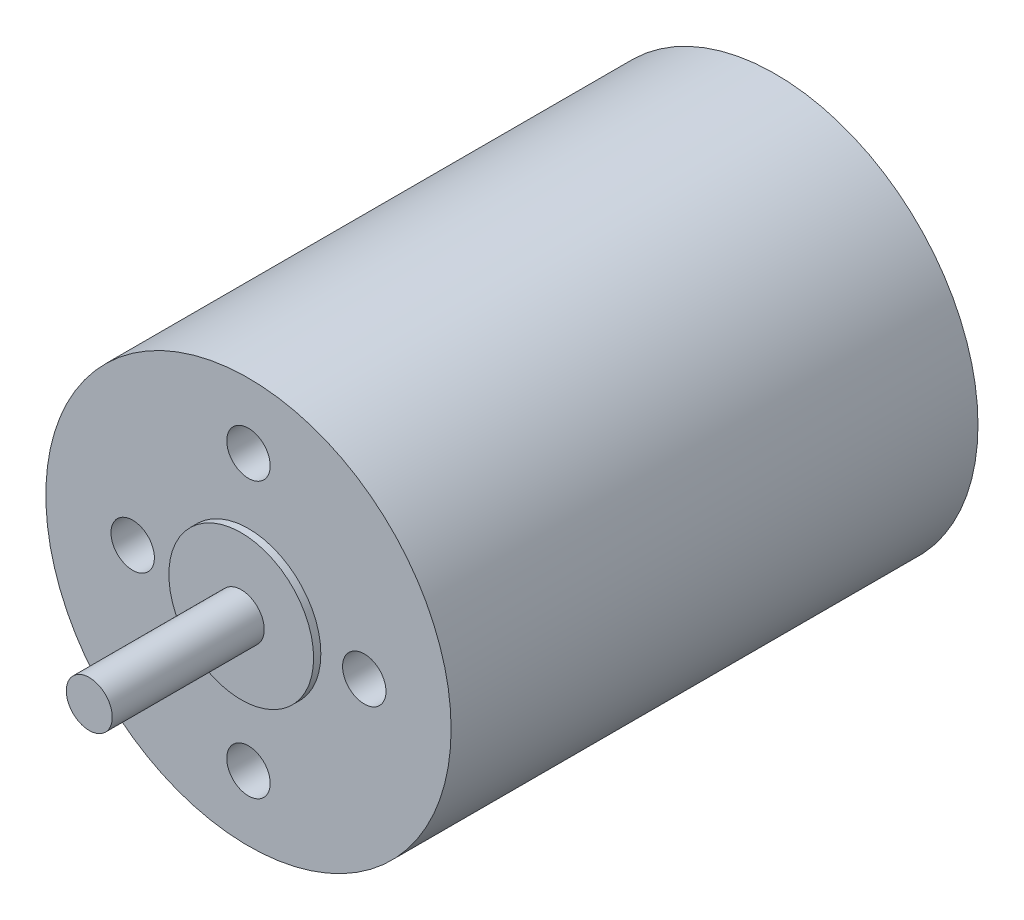
SolidWorks part; units mm, degrees
ref_plane "Front Plane" through (0, 0, 0) normal (0, 0, 1) x (1, 0, 0)
ref_plane "Top Plane" through (0, 0, 0) normal (0, 1, 0) x (1, 0, 0)
ref_plane "Right Plane" through (0, 0, 0) normal (1, 0, 0) x (0, 0, -1)
sketch "Sketch1" plane through (0, 0, 0) normal (0, 0, 1) x (1, 0, 0)
  circle A0 centre (0, 0) radius 14
  dimension "D1" = 28
extrude "Boss-Extrude1" add sketch "Sketch1" along normal blind 36.4
sketch "Sketch2" plane through (0, 0, 36.4) normal (0, 0, 1) x (1, 0, 0)
  circle A0 centre (0, 0) radius 5
  dimension "D1" = 10
extrude "Boss-Extrude2" add sketch "Sketch2" along normal blind 0.5
sketch "Sketch3" plane through (0, 0, 36.9) normal (0, 0, 1) x (1, 0, 0)
  circle A0 centre (0, 0) radius 1.5875
  dimension "D1" = 3.175
extrude "Boss-Extrude3" add sketch "Sketch3" along normal blind 10.5
hole_wizard "Ø3.0 (3) Diameter Hole1" positions "Sketch5" profile "Sketch7" hole size "Ø3.0" standard "ANSI Metric"
sketch "Sketch5" plane through (0, 0, 36.4) normal (0, 0, 1) x (1, 0, 0)
  point P0 (0, 9.5)
  point P2 (0, -9.5)
  point P4 (8, 0)
  point P6 (-8, 0)
  dimension "D1" = 19
  dimension "D2" = 9.5
  dimension "D3" = 16
  dimension "D4" = 8
sketch "Sketch7" plane through (0, 9.5, 36.4) normal (1, 0, 0) x (0, -1, 0)
  line L0 (0, 0) -> (0, 4.9013)
  line L1 (0, 4.9013) -> (1.5, 4)
  line L2 (1.5, 4) -> (1.5, 0)
  line L5 (1.5, 0) -> (0, 0)
  line L10 (0, 4.9013) -> (-1.5, 4) construction
  line L11 (0, -6.35) -> (0, 107.95) construction
  dimension "Hole Dia." = 3
  dimension "Hole Depth" = 4
  dimension "Drill Angle" = 118
